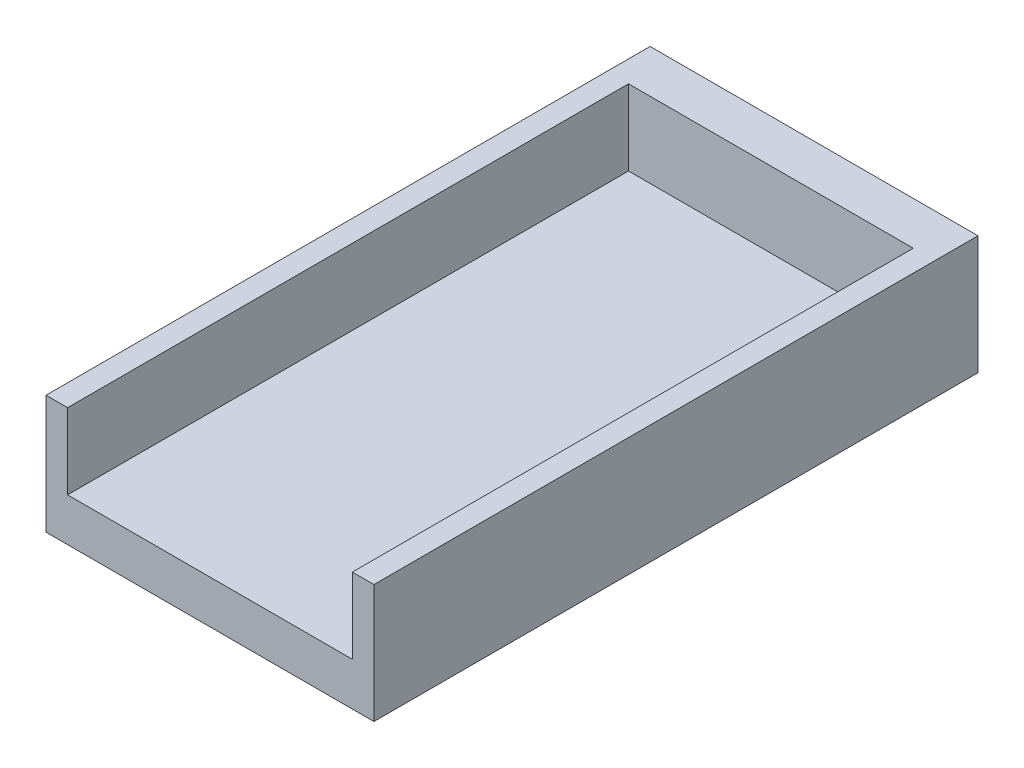
SolidWorks part; units mm, degrees
ref_plane "Front Plane" through (0, 0, 0) normal (0, 0, 1) x (1, 0, 0)
ref_plane "Top Plane" through (0, 0, 0) normal (0, 1, 0) x (1, 0, 0)
ref_plane "Right Plane" through (0, 0, 0) normal (1, 0, 0) x (0, 0, -1)
sketch "Sketch1" plane through (0, 0, 0) normal (0, 1, 0) x (1, 0, 0)
  line L1 (-7.6, 14) -> (7.6, 14)
  line L2 (-7.6, 14) -> (-7.6, -14)
  line L3 (-7.6, -14) -> (7.6, -14)
  line L4 (7.6, 14) -> (7.6, -14)
  point P4 (0, 14)
  point P5 (-7.6, 0)
  dimension "D1" = 15.2
  dimension "D2" = 28
extrude "Boss-Extrude1" add sketch "Sketch1" along normal blind 5.5
sketch "Sketch2" plane through (0, 0, 0) normal (0, 0, 1) x (1, 0, 0)
  line L1 (-6.6, 7.5) -> (6.6, 7.5)
  line L2 (-6.6, 7.5) -> (-6.6, 2)
  line L3 (-6.6, 2) -> (6.6, 2)
  line L4 (6.6, 7.5) -> (6.6, 2)
  point P5 (0, 2)
  dimension "D1" = 2
  dimension "D2" = 7.5
  dimension "D3" = 13.2
extrude "Cut-Extrude1" cut sketch "Sketch2" against normal blind 12 and the other way blind 14
